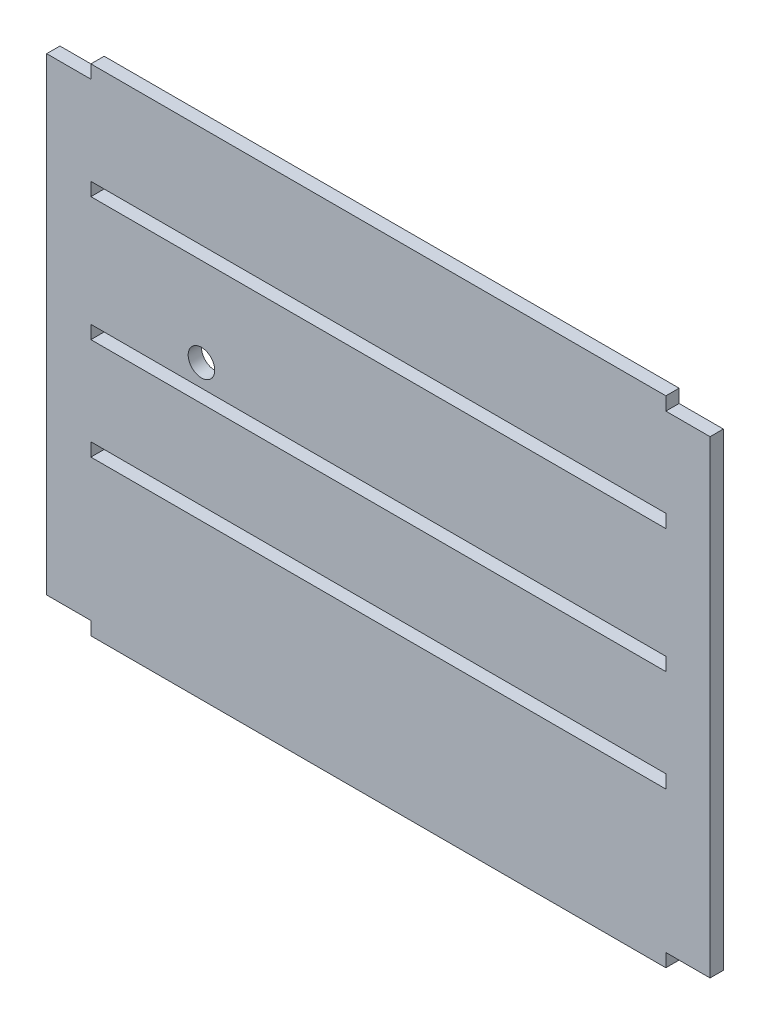
SolidWorks part; units mm, degrees
ref_plane "Front Plane" through (0, 0, 0) normal (0, 0, 1) x (1, 0, 0)
ref_plane "Top Plane" through (0, 0, 0) normal (0, 1, 0) x (1, 0, 0)
ref_plane "Right Plane" through (0, 0, 0) normal (1, 0, 0) x (0, 0, -1)
sketch "Sketch1" plane through (0, 0, 0) normal (0, 0, 1) x (1, 0, 0)
  line L0 (-59.697, -16.5185) -> (70.303, -16.5185)
  line L1 (-69.697, 34.4815) -> (80.303, 34.4815)
  line L2 (-69.697, 34.4815) -> (-69.697, -77.5185)
  line L3 (-69.697, -77.5185) -> (80.303, -77.5185)
  line L4 (80.303, 34.4815) -> (80.303, -77.5185)
  line L7 (-69.697, 31.4815) -> (-59.697, 31.4815)
  line L8 (-59.697, 34.4815) -> (-59.697, 31.4815)
  line L11 (-69.697, -74.5185) -> (-59.697, -74.5185)
  line L12 (-59.697, -77.5185) -> (-59.697, -74.5185)
  line L15 (80.303, 31.4815) -> (70.303, 31.4815)
  line L16 (70.303, 34.4815) -> (70.303, 31.4815)
  line L19 (80.303, -74.5185) -> (70.303, -74.5185)
  line L20 (70.303, -77.5185) -> (70.303, -74.5185)
  line L21 (-59.697, -39.5185) -> (70.303, -39.5185)
  line L22 (-59.697, -39.5185) -> (-59.697, -42.5185)
  line L23 (-59.697, -42.5185) -> (70.303, -42.5185)
  line L24 (70.303, -39.5185) -> (70.303, -42.5185)
  line L25 (-59.697, -16.5185) -> (-59.697, -19.5185)
  line L26 (-59.697, -19.5185) -> (70.303, -19.5185)
  line L27 (70.303, -16.5185) -> (70.303, -19.5185)
  line L28 (-59.697, 11.4815) -> (70.303, 11.4815)
  line L29 (-59.697, 11.4815) -> (-59.697, 8.4815)
  line L30 (-59.697, 8.4815) -> (70.303, 8.4815)
  line L31 (70.303, 11.4815) -> (70.303, 8.4815)
  circle A0 centre (-34.697, -11.5185) radius 3
  point P20 (-64.697, -74.5185)
  dimension "D22" = 25
  dimension "D1" = 150
  dimension "D2" = 112
  dimension "D3" = 10
  dimension "D4" = 3
  dimension "D5" = 10
  dimension "D6" = 3
  dimension "D7" = 10
  dimension "D8" = 3
  dimension "D9" = 3
  dimension "D10" = 10
  dimension "D11" = 130
  dimension "D12" = 3
  dimension "D13" = 32
  dimension "D14" = 10
  dimension "D15" = 130
  dimension "D16" = 130
  dimension "D17" = 20
  dimension "D18" = 10
  dimension "D19" = 25
  dimension "D20" = 10
  dimension "D21" = 20
  dimension "D23" = 5
extrude "Boss-Extrude1" add sketch "Sketch1" along normal blind 3 contours L3 L20 L19 L4 L15 L16 L1 L8 L7 L2 L11 L12 A0 L21 L24 L23 L22 L0 L27 L26 L25 L28 L31 L30 L29
